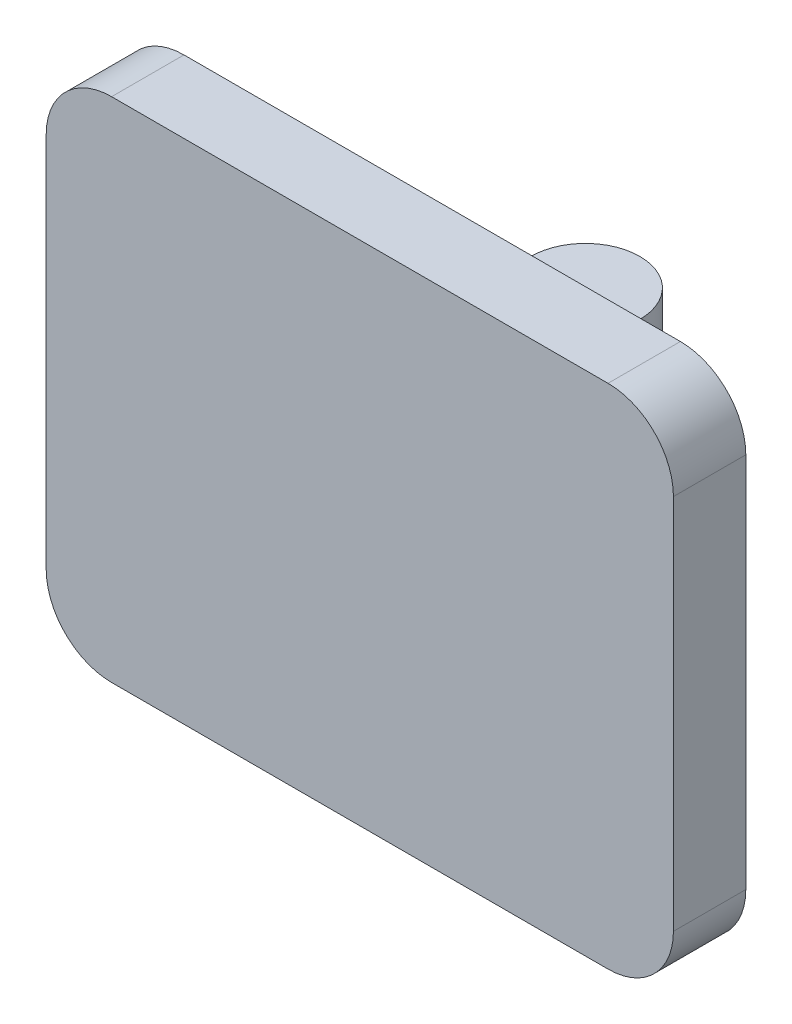
SolidWorks part; units mm, degrees
ref_plane "Front Plane" through (0, 0, 0) normal (0, 0, 1) x (1, 0, 0)
ref_plane "Top Plane" through (0, 0, 0) normal (0, 1, 0) x (1, 0, 0)
ref_plane "Right Plane" through (0, 0, 0) normal (1, 0, 0) x (0, 0, -1)
sketch "Sketch1" plane through (0, 0, 0) normal (0, 0, 1) x (1, 0, 0)
  line L1 (-113.85, 116.35) -> (113.85, 116.35)
  line L2 (-143.85, 86.35) -> (-143.85, -86.35)
  line L3 (-113.85, -116.35) -> (113.85, -116.35)
  line L4 (143.85, 86.35) -> (143.85, -86.35)
  line L5 (-143.85, 116.35) -> (143.85, -116.35) construction
  line L6 (-143.85, -116.35) -> (143.85, 116.35) construction
  arc A0 (113.85, -116.35) -> (143.85, -86.35) centre (113.85, -86.35) ccw
  arc A1 (113.85, 116.35) -> (143.85, 86.35) centre (113.85, 86.35) cw
  arc A2 (-113.85, 116.35) -> (-143.85, 86.35) centre (-113.85, 86.35) ccw
  arc A3 (-143.85, -86.35) -> (-113.85, -116.35) centre (-113.85, -86.35) ccw
  point P0 (0, 0)
  dimension "D3" = 30
  dimension "D1" = 287.7
  dimension "D2" = 232.7
extrude "Boss-Extrude1" add sketch "Sketch1" along normal blind 33.2
sketch "Sketch2" plane through (0, 0, 0) normal (0, 0, -1) x (-1, 0, 0)
  line L0 (-56.845, -87.4) -> (56.845, -87.4) construction
  line L1 (-56.845, -80.9) -> (56.845, -80.9)
  line L2 (-56.845, -93.9) -> (56.845, -93.9)
  arc A0 (-56.845, -80.9) -> (-56.845, -93.9) centre (-56.845, -87.4) ccw
  arc A1 (56.845, -93.9) -> (56.845, -80.9) centre (56.845, -87.4) ccw
  point P2 (0, -87.4)
  point P7 (-13.995, -87.4)
  point P8 (14.005, -87.4)
  dimension "D1" = 113.69
  dimension "D2" = 42.85
  dimension "D3" = 70.85
  dimension "D4" = 13
  dimension "D5" = 87.4
extrude "Boss-Extrude2" add sketch "Sketch2" along normal blind 4.8
hole_wizard "M5x0.8 Tapped Hole1" positions "Sketch4" profile "Sketch3" tap size "M5x0.8" standard "ANSI Metric"
sketch "Sketch4" plane through (0, 0, -4.8) normal (0, 0, -1) x (-1, 0, 0)
  point P0 (-13.995, -87.4)
  point P2 (14.005, -87.4)
sketch "Sketch3" plane through (13.995, -87.4, -4.8) normal (1, 0, 0) x (0, 1, 0)
  line L0 (0, 0) -> (0, 4.799)
  line L1 (0, 4.799) -> (2.1, 4.799)
  line L2 (2.1, 4.799) -> (2.1, 0)
  line L5 (2.1, 0) -> (0, 0)
  line L10 (0, 4.799) -> (-2.1, 4.799) construction
  line L11 (0, -6.35) -> (0, 107.95) construction
  dimension "Tap Drill Dia." = 4.2
  dimension "Tap Drill Depth" = 4.799
  dimension "Drill Angle" = 180
cosmetic thread "Hole Thread1" parameters "D1"=4.8, "D2"=5
cosmetic thread "Hole Thread2" parameters "D1"=4.8, "D2"=5
sketch "Sketch6" plane through (0, 116.35, 0) normal (0, 1, 0) x (1, 0, 0)
  line L1 (113.85, -33.2) -> (-113.85, -33.2) construction
  line L2 (47.95, 6.6146) -> (47.95, 0)
  line L3 (113.85, 0) -> (-113.85, 0) construction
  line L4 (47.95, 0) -> (31.95, 0)
  line L5 (31.95, 0) -> (31.95, 6.6146)
  line L6 (39.95, 30.3) -> (39.95, 0) construction
  circle A0 centre (39.95, 30.3) radius 25
  dimension "D1" = 50
  dimension "D2" = 63.5
  dimension "D3" = 103.9
  dimension "D4" = 16
extrude "Boss-Extrude3" add sketch "Sketch6" against normal blind 73.9 from offset 30.8 offset against normal yes
sketch "Sketch7" plane through (0, 11.65, 0) normal (0, -1, 0) x (1, 0, 0)
  circle A0 centre (39.95, -30.3) radius 25
extrude "Boss-Extrude4" add sketch "Sketch7" along normal blind 100 draft 7
